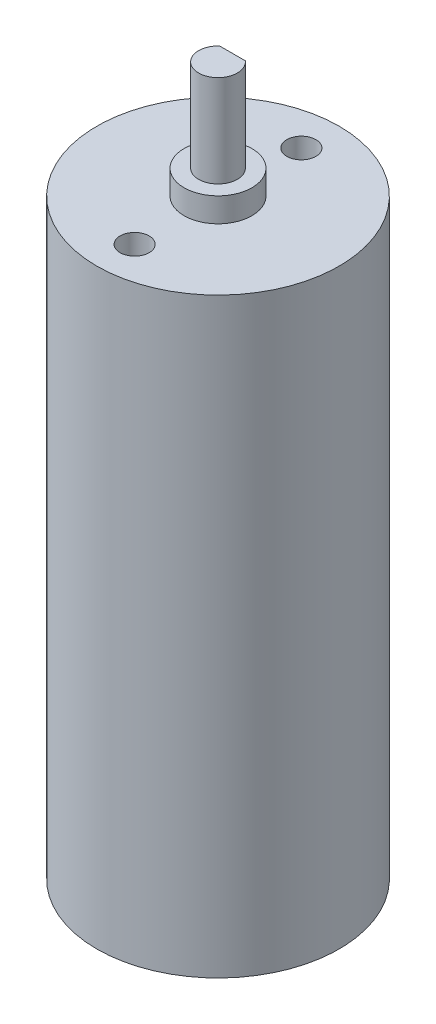
SolidWorks part; units mm, degrees
ref_plane "Front Plane" through (0, 0, 0) normal (0, 0, 1) x (1, 0, 0)
ref_plane "Top Plane" through (0, 0, 0) normal (0, 1, 0) x (1, 0, 0)
ref_plane "Right Plane" through (0, 0, 0) normal (1, 0, 0) x (0, 0, -1)
sketch "Sketch1" plane through (0, 0, 0) normal (0, 1, 0) x (1, 0, 0)
  circle A0 centre (0, 0) radius 12.5
  dimension "D1" = 25
extrude "Boss-Extrude1" add sketch "Sketch1" along normal blind 61
sketch "Sketch2" plane through (0, 61, 0) normal (0, 1, 0) x (1, 0, 0)
  circle A0 centre (0, 0) radius 3.5
  dimension "D1" = 7
extrude "Boss-Extrude2" add sketch "Sketch2" along normal blind 2.5
sketch "Sketch3" plane through (0, 63.5, 0) normal (0, 1, 0) x (1, 0, 0)
  circle A0 centre (0, 0) radius 2
  dimension "D1" = 4
extrude "Boss-Extrude3" add sketch "Sketch3" along normal blind 1.5
sketch "Sketch4" plane through (0, 65, 0) normal (0, 1, 0) x (1, 0, 0)
  line L0 (-1.3229, 1.5) -> (1.3229, 1.5)
  arc A0 (-1.3229, 1.5) -> (1.3229, 1.5) centre (0, 0) ccw
  point P5 (0, 1.5)
  dimension "D1" = 1.5
extrude "Boss-Extrude4" add sketch "Sketch4" along normal blind 8
sketch "Sketch5" plane through (0, 61, 0) normal (0, 1, 0) x (1, 0, 0)
  circle A0 centre (0, 8.6) radius 1.5
  circle A1 centre (0, -8.6) radius 1.5
  dimension "D1" = 3
  dimension "D2" = 3
  dimension "D3" = 17.2
  dimension "D4" = 8.6
extrude "Cut-Extrude1" cut sketch "Sketch5" against normal blind 3
